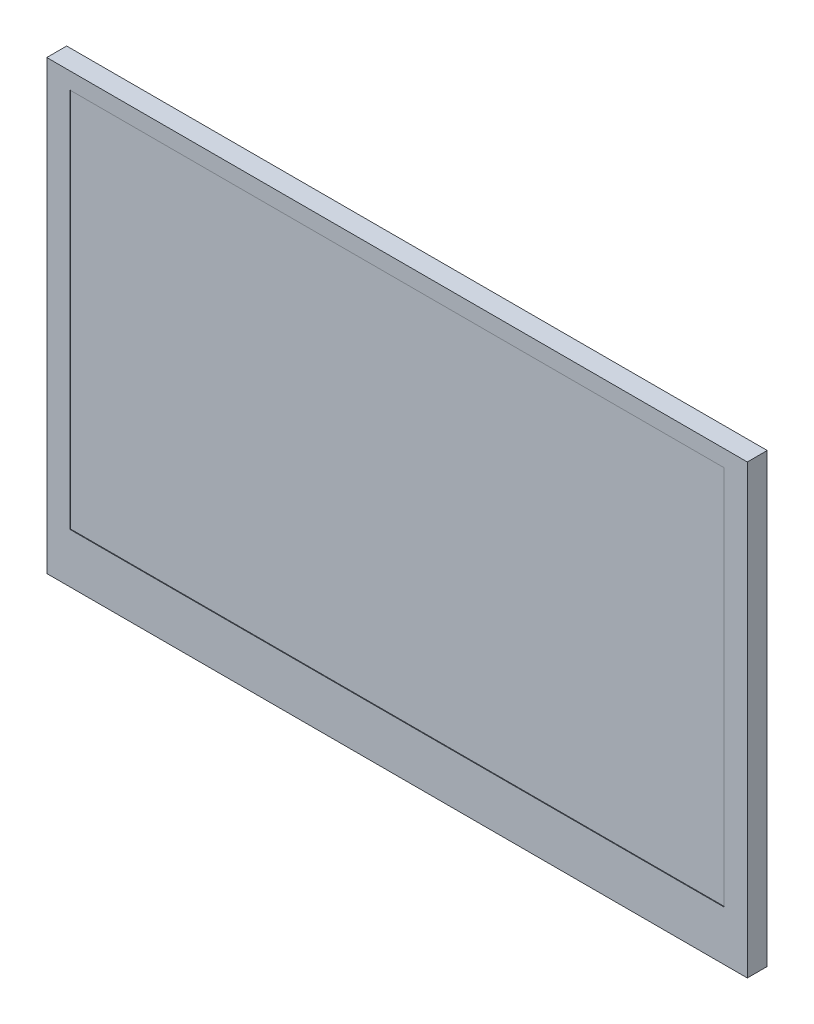
SolidWorks part; units mm, degrees
ref_plane "前视基准面" through (0, 0, 0) normal (0, 0, 1) x (1, 0, 0)
ref_plane "上视基准面" through (0, 0, 0) normal (0, 1, 0) x (1, 0, 0)
ref_plane "右视基准面" through (0, 0, 0) normal (1, 0, 0) x (0, 0, -1)
ref_plane "基准面4" through (0, 0, 3) normal (0, 0, 1) x (1, 0, 0)
sketch "草图1" plane through (0, 0, 3) normal (0, 0, 1) x (1, 0, 0)
  line L0 (-52.75, 33.65) -> (-52.75, -33.65)
  line L1 (-52.75, -33.65) -> (52.75, -33.65)
  line L2 (52.75, -33.65) -> (52.75, 33.65)
  line L3 (52.75, 33.65) -> (-52.75, 33.65)
extrude "凸台-拉伸1" add sketch "草图1" against normal blind 3
sketch "草图2" plane through (0, -33.65, 0) normal (0, -1, 0) x (1, 0, 0)
  line L0 (12.75, 2) -> (12.75, -8.5493)
  line L1 (12.75, -8.5493) -> (-32.75, -8.5493)
  line L2 (-32.75, -8.5493) -> (-32.75, 2)
  line L3 (-32.75, 2) -> (12.75, 2)
extrude "凸台-拉伸2" add sketch "草图2" along normal blind 0.1
sketch "草图3" plane through (0, 0, 3) normal (0, 0, 1) x (1, 0, 0)
  line L0 (-49.25, -26.15) -> (49.25, -26.15)
  line L1 (49.25, -26.15) -> (49.25, 31.15)
  line L2 (49.25, 31.15) -> (-49.25, 31.15)
  line L3 (-49.25, 31.15) -> (-49.25, -26.15)
extrude "切除-拉伸1" cut sketch "草图3" against normal blind 0.1
